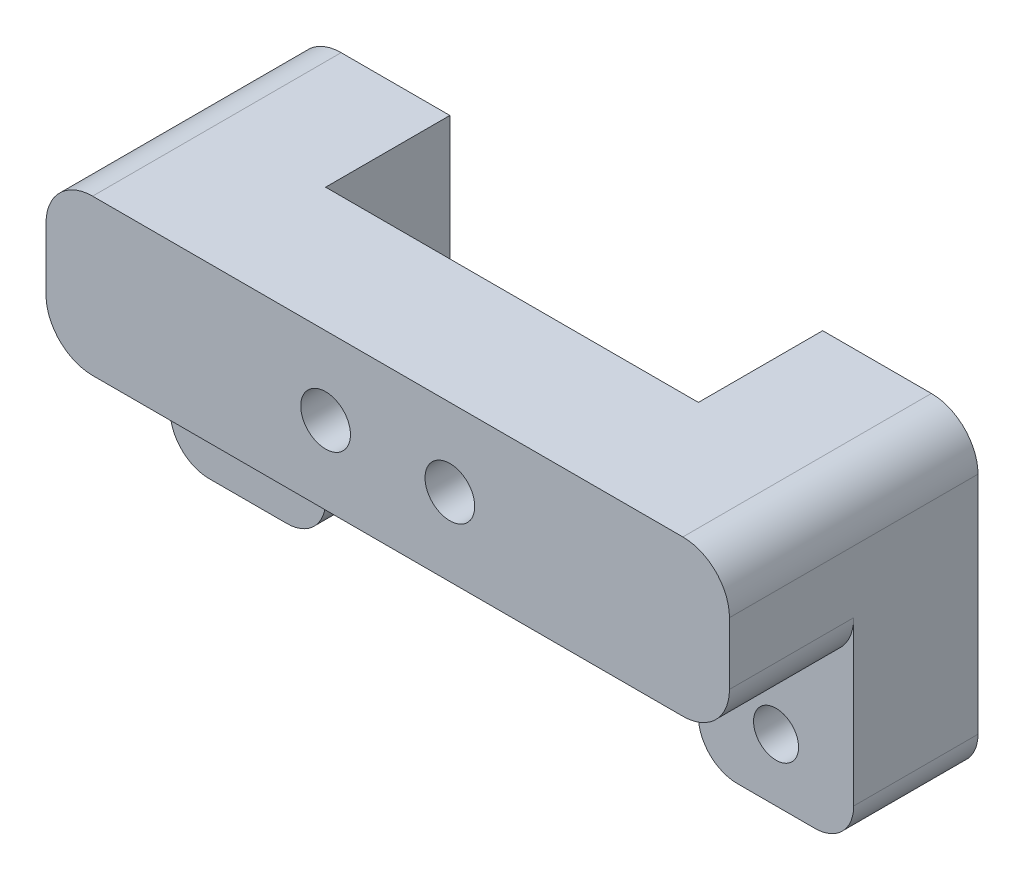
SolidWorks part; units mm, degrees
ref_plane "Front" through (0, 0, 0) normal (0, 0, 1) x (1, 0, 0)
ref_plane "Top" through (0, 0, 0) normal (0, 1, 0) x (1, 0, 0)
ref_plane "Right" through (0, 0, 0) normal (1, 0, 0) x (0, 0, -1)
sketch "Sketch1" plane through (0, 0, 0) normal (0, 0, 1) x (1, 0, 0)
  line L1 (0, 0) -> (44, 0)
  line L2 (0, 0) -> (0, -10)
  line L3 (0, -10) -> (44, -10)
  line L4 (44, 0) -> (44, -10)
  dimension "D1" = 10
  dimension "D2" = 44
extrude "Boss-Extrude1" add sketch "Sketch1" along normal blind 8
sketch "Sketch4" plane through (0, 0, 0) normal (0, 0, -1) x (-1, 0, 0)
  line L0 (-44, 0) -> (0, 0) construction
  line L1 (0, -10) -> (-10, -10)
  line L2 (0, -10) -> (0, 0)
  line L3 (0, 0) -> (-10, 0)
  line L4 (-10, -10) -> (-10, 0)
  line L6 (-44, -10) -> (-34, -10)
  line L7 (-44, -10) -> (-44, 0)
  line L8 (-44, 0) -> (-34, 0)
  line L9 (-34, -10) -> (-34, 0)
  dimension "D1" = 10
  dimension "D2" = 10
extrude "Boss-Extrude2" add sketch "Sketch4" along normal blind 8
sketch "Sketch3" plane through (0, 0, 8) normal (0, 0, 1) x (1, 0, 0)
  line L0 (0, -10) -> (44, -10) construction
  line L1 (0, 0) -> (0, -10) construction
  line L2 (44, -10) -> (44, 0) construction
  circle A0 centre (18, -5) radius 1.6
  circle A1 centre (26, -5) radius 1.6
  dimension "D1" = 3.2
  dimension "D2" = 3.2
  dimension "D3" = 5
  dimension "D4" = 5
  dimension "D5" = 18
  dimension "D6" = 18
extrude "Cut-Extrude2" cut sketch "Sketch3" against normal through all
sketch "Sketch5" plane through (0, -10, 0) normal (0, -1, 0) x (-1, 0, 0)
  line L1 (-10, 0) -> (0, 0)
  line L2 (-10, 0) -> (-10, 8)
  line L3 (-10, 8) -> (0, 8)
  line L4 (0, 0) -> (0, 8)
  line L5 (-34, 0) -> (-44, 0)
  line L6 (-34, 0) -> (-34, 8)
  line L7 (-34, 8) -> (-44, 8)
  line L8 (-44, 0) -> (-44, 8)
extrude "Boss-Extrude3" add sketch "Sketch5" along normal blind 10
sketch "Sketch6" plane through (0, 0, 0) normal (0, 0, 1) x (1, 0, 0)
  line L0 (10, -20) -> (0, -20) construction
  line L1 (44, -20) -> (34, -20) construction
  line L2 (44, -20) -> (44, -10) construction
  line L3 (10, -20) -> (10, -10) construction
  circle A0 centre (5, -16) radius 1.45
  circle A1 centre (39, -16) radius 1.45
  dimension "D1" = 2.9
  dimension "D2" = 2.9
  dimension "D3" = 4
  dimension "D4" = 4
  dimension "D5" = 5
  dimension "D6" = 5
extrude "Cut-Extrude3" cut sketch "Sketch6" against normal through all
fillet "Fillet2" radius 2.5 4 edges at (44, -20, -4) (34, -20, -4) (10, -20, -4) (0, -20, -4)
fillet "Fillet1" radius 3 4 edges at (0, -10, 4) (44, -10, 4) (44, 0, 0) (0, 0, 0)
